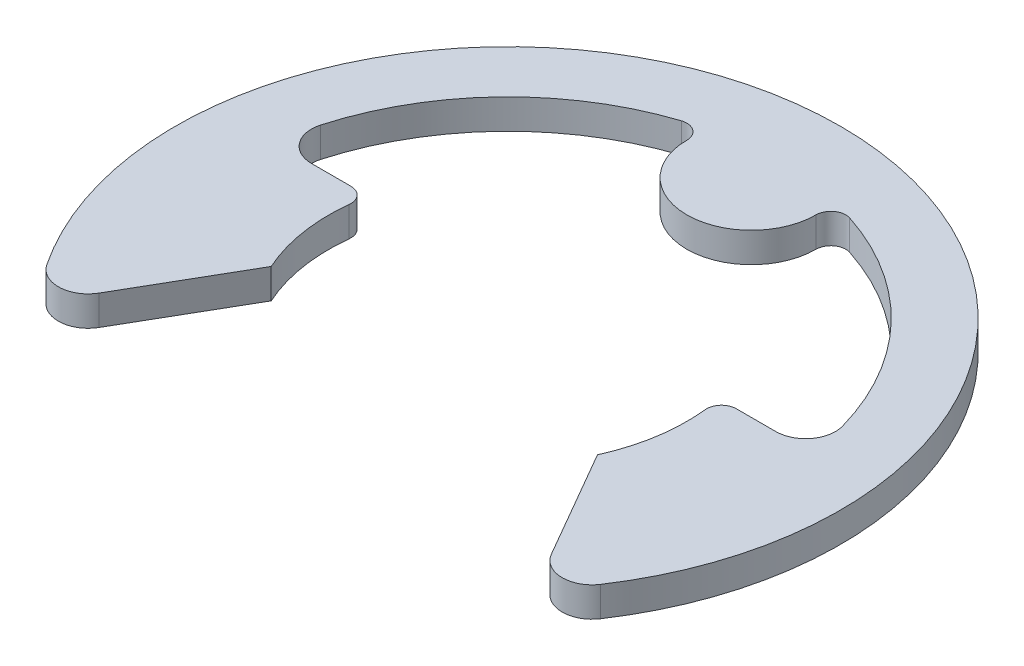
SolidWorks part; units mm, degrees
material "合金钢"
ref_plane "前视基准面" through (0, 0, 0) normal (0, 0, 1) x (1, 0, 0)
ref_plane "上视基准面" through (0, 0, 0) normal (0, 1, 0) x (1, 0, 0)
ref_plane "右视基准面" through (0, 0, 0) normal (1, 0, 0) x (0, 0, -1)
other "Configuration Table"
sketch "草图1" plane through (0, 0, 0) normal (0, 1, 0) x (1, 0, 0)
  line L0 (12.9244, 2.4) -> (15.5702, 2.4)
  line L1 (-10.94, -4.9312) -> (-15.1655, -12.25)
  line L2 (15.1655, -12.25) -> (10.94, -4.9312)
  line L3 (-15.5702, 2.4) -> (-12.9244, 2.4)
  arc A1 (-15.1655, -12.25) -> (-18.5624, -12.3584) centre (-16.8976, -11.25) cw
  arc A2 (-18.5624, -12.3584) -> (18.5624, -12.3584) centre (0, 0) cw
  arc A3 (18.5624, -12.3584) -> (15.1655, -12.25) centre (16.8976, -11.25) cw
  arc A4 (10.94, -4.9312) -> (11.9302, 1.2923) centre (0, 0) ccw
  arc A5 (11.9302, 1.2923) -> (12.9244, 2.4) centre (12.9244, 1.4) cw
  arc A6 (15.5702, 2.4) -> (17.4949, 4.9439) centre (15.5702, 4.4) ccw
  arc A7 (17.4949, 4.9439) -> (5.6421, 17.2823) centre (0, 0) ccw
  arc A8 (5.6421, 17.2823) -> (4.3317, 16.3317) centre (5.3317, 16.3317) ccw
  arc A9 (4.3317, 16.3317) -> (-4.3317, 16.3317) centre (0, 16.3317) cw
  arc A10 (-4.3317, 16.3317) -> (-5.6421, 17.2823) centre (-5.3317, 16.3317) ccw
  arc A11 (-5.6421, 17.2823) -> (-17.4949, 4.9439) centre (0, 0) ccw
  arc A12 (-17.4949, 4.9439) -> (-15.5702, 2.4) centre (-15.5702, 4.4) ccw
  arc A13 (-12.9244, 2.4) -> (-11.9302, 1.2923) centre (-12.9244, 1.4) cw
  arc A14 (-11.9302, 1.2923) -> (-10.94, -4.9312) centre (0, 0) ccw
  point P2 (0, 12)
  dimension "d2" = 24
  dimension "d3" = 44.6
  dimension "dt" = 36.36
  dimension "r2" = 1
  dimension "r1" = 2
  dimension "r3" = 2
  dimension "r4" = 1
  dimension "a" = 21.88
  dimension "theta" = 60
  dimension "D1" = 2.4
  dimension "D7" = 12
extrude "凸台-拉伸1" add sketch "草图1" along normal blind 2
equation "\"dt@草图1\"= \"d2@草图1\" + 0.6 * ( \"d3@草图1\" - \"d2@草图1\" )"
equation "\"D7@草图1\"= 0.5 * \"d2@草图1\""
equation "\"r4@草图1\"= \"r2@草图1\""
equation "\"r3@草图1\"= \"r1@草图1\""
equation "\"r2@草图1\"= 0.5 * \"r1@草图1\""
